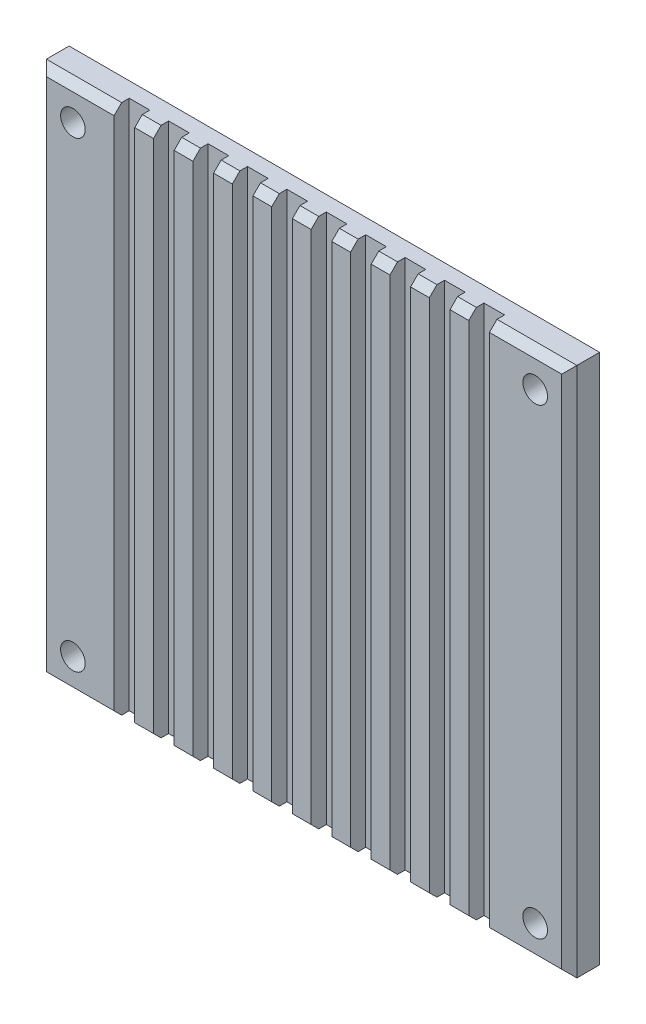
SolidWorks part; units mm, degrees
material "Plain Carbon Steel"
ref_plane "Front Plane" through (0, 0, 0) normal (0, 0, 1) x (1, 0, 0)
ref_plane "Top Plane" through (0, 0, 0) normal (0, 1, 0) x (1, 0, 0)
ref_plane "Right Plane" through (0, 0, 0) normal (1, 0, 0) x (0, 0, -1)
sketch "Sketch1" plane through (0, 0, 0) normal (0, 0, 1) x (1, 0, 0)
  line L1 (0, 0) -> (70, 0)
  line L2 (0, 0) -> (0, 70)
  line L3 (0, 70) -> (70, 70)
  line L4 (70, 0) -> (70, 70)
  line L5 (4.5, 65.5) -> (65.5, 65.5) construction
  line L6 (4.5, 65.5) -> (4.5, 4.5) construction
  line L7 (4.5, 4.5) -> (65.5, 4.5) construction
  line L8 (65.5, 65.5) -> (65.5, 4.5) construction
  circle A0 centre (4.5, 65.5) radius 1.625
  circle A1 centre (65.5, 65.5) radius 1.625
  circle A2 centre (65.5, 4.5) radius 1.625
  circle A3 centre (4.5, 4.5) radius 1.625
  point P9 (35, 65.5)
  point P10 (35, 70)
  point P11 (4.5, 35)
  point P12 (0, 35)
  dimension "D4" = 3.25
  dimension "D1" = 70
  dimension "D2" = 70
  dimension "D3" = 61
extrude "Boss-Extrude1" add sketch "Sketch1" along normal blind 4
sketch "Sketch2" plane through (0, 0, 4) normal (0, 0, 1) x (1, 0, 0)
  line L0 (70, 70) -> (0, 70) construction
  line L1 (9.9338, 70) -> (12.6595, 70)
  line L2 (9.9338, 70) -> (9.9338, 0)
  line L3 (9.9338, 0) -> (12.6595, 0)
  line L4 (12.6595, 70) -> (12.6595, 0)
  line L5 (0, 0) -> (70, 0) construction
  line L6 (15.1338, 70) -> (15.1338, 0)
  line L7 (15.1338, 70) -> (17.8595, 70)
  line L8 (17.8595, 70) -> (17.8595, 0)
  line L9 (15.1338, 0) -> (17.8595, 0)
  line L10 (20.3338, 70) -> (20.3338, 0)
  line L11 (20.3338, 70) -> (23.0595, 70)
  line L12 (23.0595, 70) -> (23.0595, 0)
  line L13 (20.3338, 0) -> (23.0595, 0)
  line L14 (25.5338, 70) -> (25.5338, 0)
  line L15 (25.5338, 70) -> (28.2595, 70)
  line L16 (28.2595, 70) -> (28.2595, 0)
  line L17 (25.5338, 0) -> (28.2595, 0)
  line L18 (30.7338, 70) -> (30.7338, 0)
  line L19 (30.7338, 70) -> (33.4595, 70)
  line L20 (33.4595, 70) -> (33.4595, 0)
  line L21 (30.7338, 0) -> (33.4595, 0)
  line L22 (35.9338, 70) -> (35.9338, 0)
  line L23 (35.9338, 70) -> (38.6595, 70)
  line L24 (38.6595, 70) -> (38.6595, 0)
  line L25 (35.9338, 0) -> (38.6595, 0)
  line L26 (41.1338, 70) -> (41.1338, 0)
  line L27 (41.1338, 70) -> (43.8595, 70)
  line L28 (43.8595, 70) -> (43.8595, 0)
  line L29 (41.1338, 0) -> (43.8595, 0)
  line L30 (46.3338, 70) -> (46.3338, 0)
  line L31 (46.3338, 70) -> (49.0595, 70)
  line L32 (49.0595, 70) -> (49.0595, 0)
  line L33 (46.3338, 0) -> (49.0595, 0)
  line L34 (51.5338, 70) -> (51.5338, 0)
  line L35 (51.5338, 70) -> (54.2595, 70)
  line L36 (54.2595, 70) -> (54.2595, 0)
  line L37 (51.5338, 0) -> (54.2595, 0)
  line L38 (56.7338, 70) -> (56.7338, 0)
  line L39 (56.7338, 70) -> (59.4595, 70)
  line L40 (59.4595, 70) -> (59.4595, 0)
  line L41 (56.7338, 0) -> (59.4595, 0)
  dimension "D2" = 5.2
  dimension "D1" = 10
extrude "Cut-Extrude1" cut sketch "Sketch2" against normal blind 2
chamfer "Chamfer1" distance 1 angle 45 24 edges at (55.4967, 0, 4) (50.2967, 0, 4) (45.0967, 0, 4) (39.8967, 0, 4) (34.6967, 0, 4) (29.4967, 0, 4) (24.2967, 0, 4) (19.0967, 0, 4) (13.8967, 0, 4) (55.4967, 70, 4) (50.2967, 70, 4) (45.0967, 70, 4) (39.8967, 70, 4) (34.6967, 70, 4) (29.4967, 70, 4) (24.2967, 70, 4) (19.0967, 70, 4) (13.8967, 70, 4) (64.7297, 70, 4) (64.7297, 0, 4) (70, 35, 4) (4.9669, 70, 4) (4.9669, 0, 4) (0, 35, 4)
